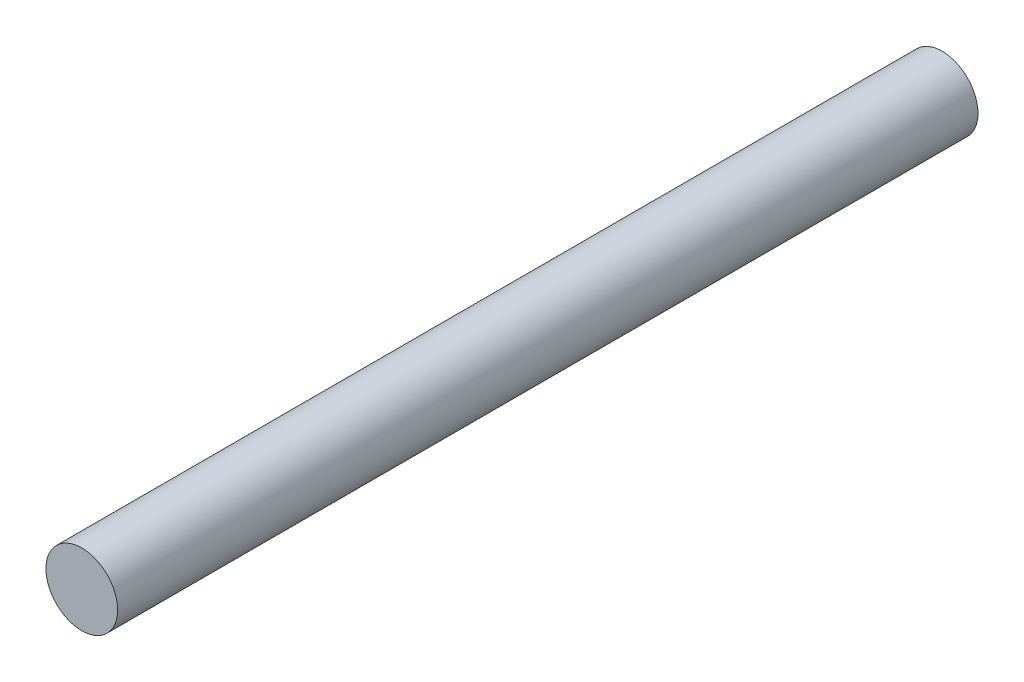
SolidWorks part; units mm, degrees
ref_plane "Front Plane" through (0, 0, 0) normal (1, 0, 0) x (0, 1, 0)
ref_plane "Top Plane" through (0, 0, 0) normal (0, 0, 1) x (0, 1, 0)
ref_plane "Right Plane" through (0, 0, 0) normal (0, 1, 0) x (-1, 0, 0)
sketch "Sketch2" plane through (0, 0, 0) normal (0, 0, 1) x (0, 1, 0)
  circle A0 centre (0, 0) radius 3
  dimension "D1" = 6
extrude "Boss-Extrude1" add sketch "Sketch2" along normal blind 72
